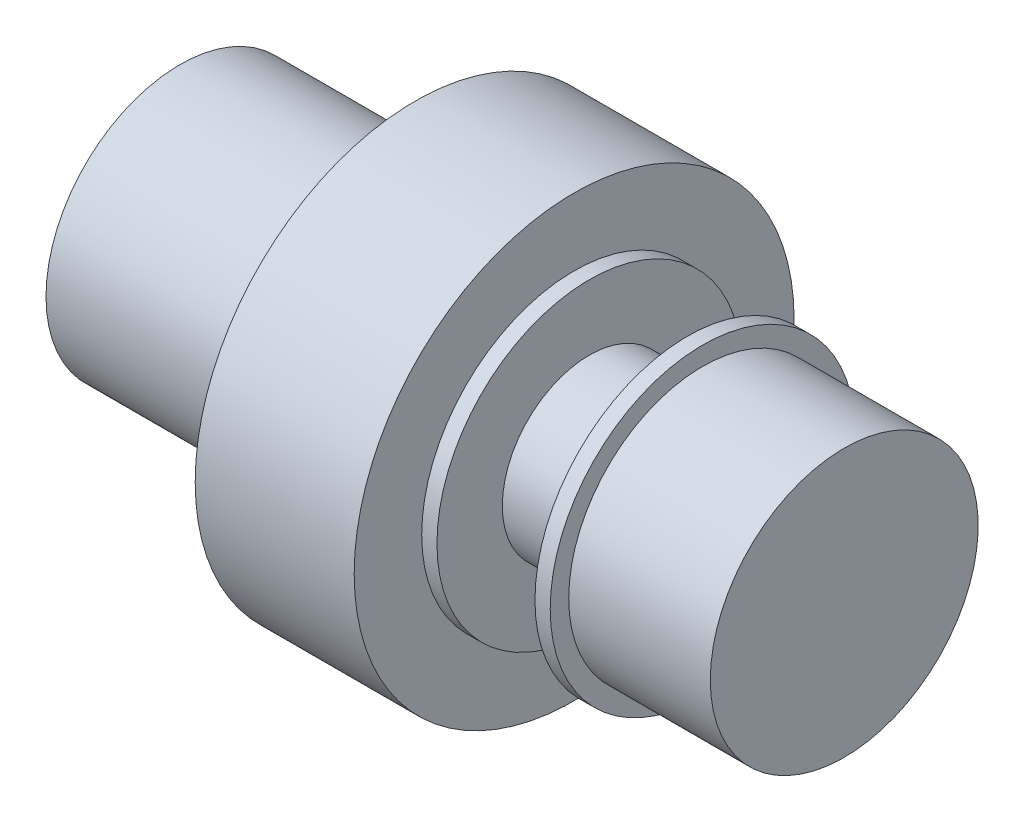
SolidWorks part; units mm, degrees
material "Acciaio al carbonio semplice"
ref_plane "Piano frontale" through (0, 0, 0) normal (0, 0, 1) x (1, 0, 0)
ref_plane "Piano superiore" through (0, 0, 0) normal (0, 1, 0) x (1, 0, 0)
ref_plane "Piano destro" through (0, 0, 0) normal (1, 0, 0) x (0, 0, -1)
sketch "Schizzo1" plane through (0, 0, 0) normal (0, 0, 1) x (1, 0, 0)
  line L0 (-1716.3243, 0) -> (84099.8918, 0) construction
  line L1 (-152.5, 0) -> (152.5, 0)
  line L2 (-152.5, 0) -> (-152.5, 61.5)
  line L3 (-152.5, 61.5) -> (-44.5, 61.5)
  line L4 (152.5, 0) -> (152.5, 61.5)
  line L5 (152.5, 61.5) -> (87.5, 61.5)
  line L6 (-44.5, 61.5) -> (-44.5, 101)
  line L7 (-44.5, 101) -> (28.5, 101)
  line L10 (28.5, 70) -> (35.5, 70)
  line L11 (35.5, 70) -> (35.5, 40)
  line L15 (80.5, 40) -> (80.5, 70)
  line L16 (80.5, 70) -> (87.5, 70)
  line L17 (87.5, 70) -> (87.5, 61.5)
  line L19 (35.5, 40) -> (80.5, 40)
  line L20 (28.5, 101) -> (28.5, 70)
  point P6 (0, 0)
  dimension "D1" = 305
  dimension "D2" = 61.5
  dimension "D3" = 108
  dimension "D5" = 39.5
  dimension "D6" = 7
  dimension "D7" = 30
  dimension "D8" = 7
  dimension "D9" = 45
  dimension "D10" = 65
  dimension "D11" = 40
revolve "Rivoluzione1" add sketch "Schizzo1" angle 360 about L0
hole_wizard "Foro per Vite M5-1" positions "Schizzo3D1" profile "Schizzo2" hole size "M5" standard "Ansi Metric"
sketch3d "Schizzo3D1"
  line L0 (0, 0, 0) -> (0, 50000, 0) construction
  line L1 (0, 0, 0) -> (0, 0, 50000) construction
  line L2 (0.0662, 96, 0) -> (-49999.9338, 96, 0) construction
  line L3 (5.2685, 0, 96) -> (-49994.7315, 0, 96) construction
  line L4 (5.8822, 0, -96) -> (-49994.1178, 0, -96) construction
  line L5 (-44.5, -96, 0) -> (-50044.5, -96, 0) construction
  point P0 (-44.5, 96, 0)
  point P2 (-44.5, 0, 96)
  point P4 (-44.5, -96, 0)
  point P6 (-44.5, 0, -96)
  point P20 (0, 0, 0)
  point P21 (-44.5, -32.1672, 90.4504)
  point P22 (-44.5, 6.5738, 95.7747)
  dimension "D1" = 96
  dimension "D2" = 96
  dimension "D3" = 96
  dimension "D4" = 96
sketch "Schizzo2" plane through (-44.5, 96, 0) normal (0, 1, 0) x (0, 0, 1)
  line L0 (0, 0) -> (0, 17)
  line L1 (0, 17) -> (2.75, 15.3476)
  line L2 (2.75, 15.3476) -> (2.75, 0.025)
  line L3 (2.75, 0.025) -> (2.775, 0)
  line L5 (2.775, 0) -> (0, 0)
  line L6 (-2.75, 0.025) -> (-2.775, 0) construction
  line L10 (0, 17) -> (-2.75, 15.3476) construction
  line L11 (0, -6.35) -> (0, 107.95) construction
  dimension "Hole Dia." = 5.5
  dimension "Hole Depth" = 17
  dimension "Near C'Sink Dia." = 5.55
  dimension "Near C'Sink Angle" = 90
  dimension "Drill Angle" = 118
